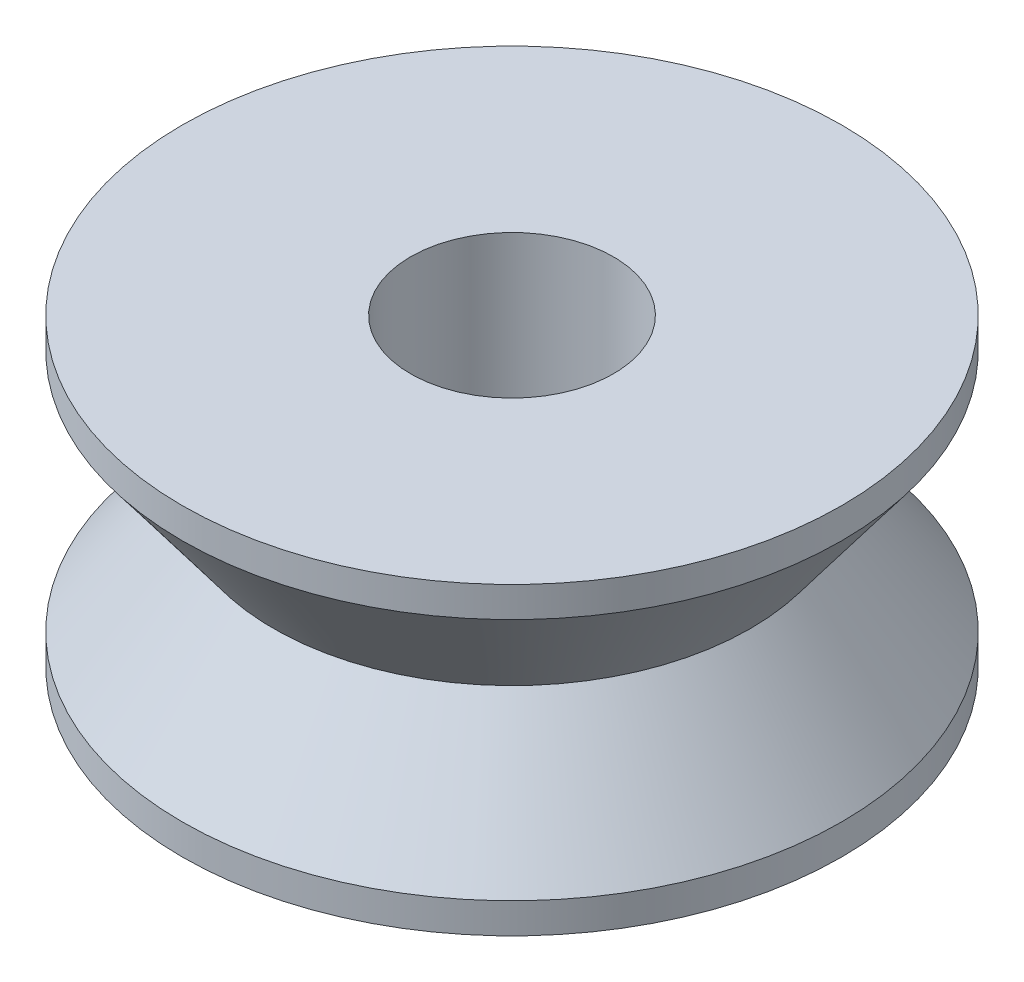
SolidWorks part; units mm, degrees
ref_plane "正面" through (0, 0, 0) normal (0, 0, 1) x (1, 0, 0)
ref_plane "平面" through (0, 0, 0) normal (0, 1, 0) x (1, 0, 0)
ref_plane "右側面" through (0, 0, 0) normal (1, 0, 0) x (0, 0, -1)
sketch "ｽｹｯﾁ1" plane through (0, 0, 0) normal (0, 0, 1) x (1, 0, 0)
  line L0 (0, -3) -> (0, 3)
  line L1 (6.5, 3) -> (6.5, 2.4)
  line L2 (0, 3) -> (6.5, 3)
  line L3 (0, 3) -> (0, -3)
  line L4 (0, -3) -> (6.5, -3)
  line L5 (6.5, 3) -> (6.5, -3) construction
  line L6 (6.5, -3) -> (6.5, -2.4)
  line L7 (6.5, 0) -> (4.7, 0) construction
  line L8 (6.5, 2.4) -> (4.7, 0)
  line L9 (4.7, 0) -> (6.5, -2.4)
  point P2 (0, 0)
  dimension "D1" = 6
  dimension "D2" = 6.5
  dimension "D3" = 0.6
  dimension "D4" = 0.6
  dimension "D5" = 1.8
revolve "回転1" add sketch "ｽｹｯﾁ1" angle 360 about L0
sketch "ｽｹｯﾁ2" plane through (0, 3, 0) normal (0, 1, 0) x (1, 0, 0)
  circle A0 centre (0, 0) radius 2
  dimension "D1" = 4
extrude "ｶｯﾄ - 押し出し1" cut sketch "ｽｹｯﾁ2" against normal blind 10
